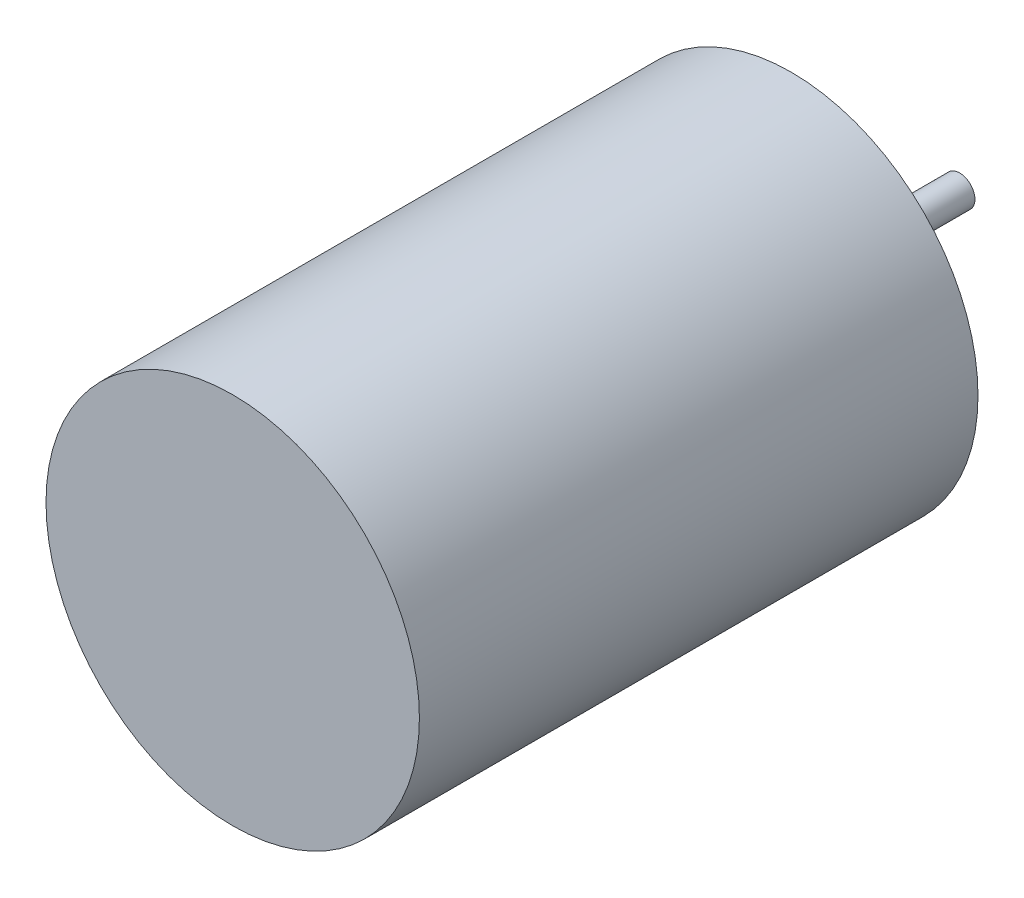
SolidWorks part; units mm, degrees
ref_plane "前视基准面" through (0, 0, 0) normal (0, 0, 1) x (1, 0, 0)
ref_plane "上视基准面" through (0, 0, 0) normal (0, 1, 0) x (1, 0, 0)
ref_plane "右视基准面" through (0, 0, 0) normal (1, 0, 0) x (0, 0, -1)
sketch "草图1" plane through (0, 0, 0) normal (0, 0, 1) x (1, 0, 0)
  circle A0 centre (0, 0) radius 12.2
  dimension "D1" = 24.4
extrude "凸台-拉伸4" add sketch "草图1" along normal blind 36.5 contours A0
sketch "草图9" plane through (0, 0, 36.5) normal (0, 0, 1) x (1, 0, 0)
sketch "草图10" plane through (0, 0, 0) normal (0, 0, -1) x (-1, 0, 0)
  circle A1 centre (0, 0) radius 1
  dimension "D2" = 2
extrude "凸台-拉伸7" add sketch "草图10" along normal blind 11 contours A1
sketch "草图11" plane through (0, 0, 0) normal (0, 0, -1) x (-1, 0, 0)
  circle A0 centre (0, 0) radius 3.225
  dimension "D1" = 6.45
extrude "凸台-拉伸8" add sketch "草图11" along normal blind 0.5 contours A0
sketch "草图13" plane through (0, 0, 0) normal (0, 0, -1) x (-1, 0, 0)
  circle A0 centre (0, 8.5046) radius 1.5
  circle A1 centre (0, -8.512) radius 1.5
  dimension "D3" = 3
  dimension "D4" = 3
  dimension "D2" = 3
extrude "切除-拉伸2" cut sketch "草图13" against normal blind 3 contours A1 | A0
sketch "草图14" plane through (0, 0, 0) normal (0, 0, -1) x (-1, 0, 0)
  line L0 (0, 8.5046) -> (0, -8.512) construction
  dimension "D1" = 17.0166
